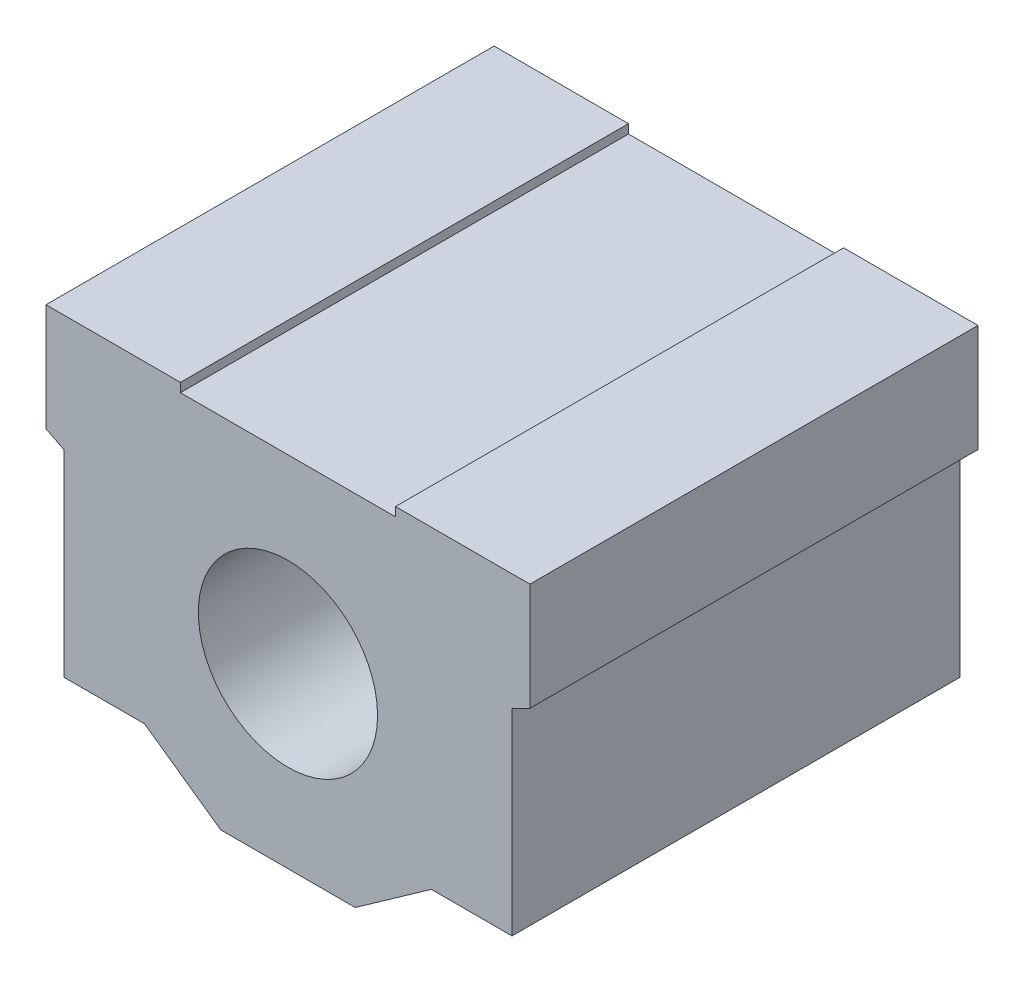
SolidWorks part; units mm, degrees
ref_plane "前视基准面" through (0, 0, 0) normal (0, 0, 1) x (1, 0, 0)
ref_plane "上视基准面" through (0, 0, 0) normal (0, 1, 0) x (1, 0, 0)
ref_plane "右视基准面" through (0, 0, 0) normal (1, 0, 0) x (0, 0, -1)
sketch "草图1" plane through (0, 0, 0) normal (0, 0, 1) x (1, 0, 0)
  line L0 (0, 42.0934) -> (0, 0) construction
  line L1 (0, 0) -> (49.8045, 0) construction
  line L2 (7.5, 0) -> (-7.5, 0)
  line L3 (-7.5, 0) -> (-16, 6)
  line L4 (-16, 6) -> (-25, 6)
  line L5 (-25, 6) -> (-25, 28)
  line L6 (-25, 28) -> (-27, 29)
  line L7 (-27, 29) -> (-27, 41)
  line L8 (-27, 41) -> (-12, 41)
  line L9 (-12, 41) -> (-12, 40)
  line L10 (-12, 40) -> (12, 40)
  line L11 (16, 6) -> (25, 6)
  line L12 (7.5, 0) -> (16, 6)
  line L13 (25, 28) -> (27, 29)
  line L14 (25, 6) -> (25, 28)
  line L15 (27, 29) -> (27, 41)
  line L16 (12, 41) -> (12, 40)
  line L17 (27, 41) -> (12, 41)
  circle A0 centre (0, 19.8) radius 10
  point P23 (0, 40)
  dimension "D1" = 20
  dimension "D2" = 54
  dimension "D3" = 41
  dimension "D4" = 19.8
  dimension "D5" = 50
  dimension "D6" = 15
  dimension "D7" = 24
  dimension "D8" = 1
  dimension "D9" = 35
  dimension "D10" = 9
  dimension "D11" = 22
  dimension "D12" = 12
extrude "凸台-拉伸1" add sketch "草图1" along normal blind 50
